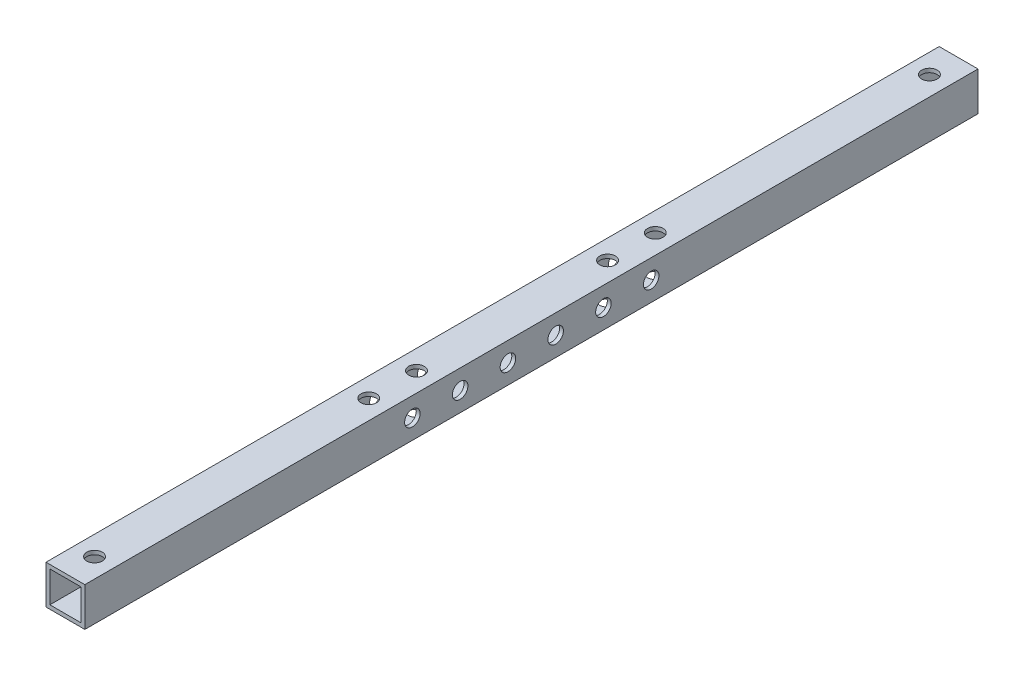
SolidWorks part; units mm, degrees
material "1060 Alloy"
ref_plane "Front Plane" through (0, 0, 0) normal (0, 0, 1) x (1, 0, 0)
ref_plane "Top Plane" through (0, 0, 0) normal (0, 1, 0) x (1, 0, 0)
ref_plane "Right Plane" through (0, 0, 0) normal (1, 0, 0) x (0, 0, -1)
sketch "Sketch1" plane through (0, 0, 0) normal (0, 0, 1) x (1, 0, 0)
  line L1 (-8, 8) -> (8, 8)
  line L2 (-8, 8) -> (-8, -8)
  line L3 (-8, -8) -> (8, -8)
  line L4 (8, 8) -> (8, -8)
  line L5 (-8, 8) -> (8, -8) construction
  line L6 (-8, -8) -> (8, 8) construction
  line L7 (-10, 10) -> (10, 10)
  line L8 (-10, 10) -> (-10, -10)
  line L9 (-10, -10) -> (10, -10)
  line L10 (10, 10) -> (10, -10)
  line L11 (-10, 10) -> (10, -10) construction
  line L12 (-10, -10) -> (10, 10) construction
  point P0 (0, 0)
  point P6 (0, 0)
  dimension "D1" = 20
  dimension "D2" = 16
  dimension "D3" = 20
  dimension "D4" = 16
extrude "Boss-Extrude1" add sketch "Sketch1" along normal blind 460.04
sketch "Sketch2" plane through (0, 10, 0) normal (0, 1, 0) x (1, 0, 0)
  circle A0 centre (0, -15) radius 4
  dimension "D2" = 8
  dimension "D1" = 15
extrude "Cut-Extrude1" cut sketch "Sketch2" against normal through all
ref_plane "Plane1" through (0, 0, 230.02) normal (0, 0, 1) x (1, 0, 0)
mirror "Mirror1" about plane through (0, 0, 230.02) normal (0, 0, 1) of "Cut-Extrude1"
sketch "Sketch5" plane through (10, 0, 0) normal (1, 0, 0) x (0, 0, -1)
  line L0 (-460.04, -10) -> (-460.04, 10) construction
  circle A0 centre (-291.33, 0) radius 4
  dimension "D1" = 8
  dimension "D2" = 168.71
extrude "Cut-Extrude2" cut sketch "Sketch5" against normal through all
pattern_linear "LPattern1" count 6 spacing 24.6 along (0, 0, -1) of "Cut-Extrude2"
sketch "Sketch6" plane through (0, 10, 0) normal (0, 1, 0) x (1, 0, 0)
  line L0 (10, -460.04) -> (-10, -460.04) construction
  circle A0 centre (0, -303.82) radius 4
  circle A1 centre (0, -279.22) radius 4
  dimension "D3" = 8
  dimension "D4" = 8
  dimension "D1" = 156.22
  dimension "D2" = 24.6
extrude "Cut-Extrude3" cut sketch "Sketch6" against normal through all
mirror "Mirror2" about plane through (0, 0, 230.02) normal (0, 0, 1) of "Cut-Extrude3"
